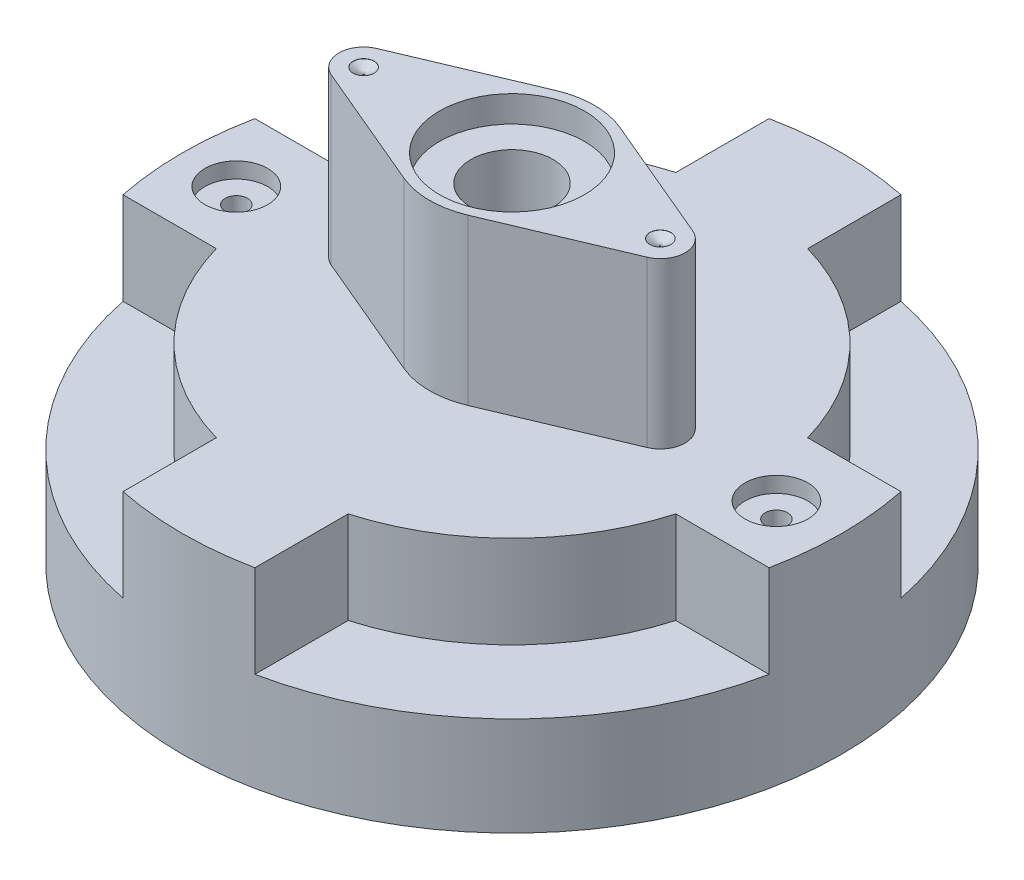
SolidWorks part; units mm, degrees
ref_plane "Front Plane" through (0, 0, 0) normal (0, 0, 1) x (1, 0, 0)
ref_plane "Top Plane" through (0, 0, 0) normal (0, 1, 0) x (1, 0, 0)
ref_plane "Right Plane" through (0, 0, 0) normal (1, 0, 0) x (0, 0, -1)
sketch "Sketch2" plane through (0, 0, 0) normal (0, 1, 0) x (1, 0, 0)
  circle A0 centre (0, 0) radius 100
  dimension "D1" = 200
extrude "Boss-Extrude1" add sketch "Sketch2" along normal blind 30
sketch "Sketch3" plane through (0, 30, 0) normal (0, 1, 0) x (1, 0, 0)
  line L0 (-20, 97.9796) -> (-20, 69.6868)
  line L2 (20, 69.6868) -> (20, 97.9796)
  line L3 (97.9796, 20) -> (69.6868, 20)
  line L4 (69.6868, -20) -> (97.9796, -20)
  line L5 (20, -97.9796) -> (20, -69.6868)
  line L6 (-20, -69.6868) -> (-20, -97.9796)
  line L7 (-97.9796, -20) -> (-69.6868, -20)
  line L8 (-69.6868, 20) -> (-97.9796, 20)
  arc A0 (-20, 69.6868) -> (-69.6868, 20) centre (0, 0) ccw
  circle A1 centre (0, 0) radius 100 construction
  arc A2 (20, 97.9796) -> (-20, 97.9796) centre (0, 0) ccw
  arc A3 (-20, 97.9796) -> (20, 97.9796) centre (0, 0) cw
  arc A4 (97.9796, -20) -> (97.9796, 20) centre (0, 0) ccw
  arc A5 (-20, -97.9796) -> (20, -97.9796) centre (0, 0) ccw
  arc A6 (-97.9796, 20) -> (-97.9796, -20) centre (0, 0) ccw
  arc A7 (-69.6868, -20) -> (-20, -69.6868) centre (0, 0) ccw
  arc A8 (69.6868, 20) -> (20, 69.6868) centre (0, 0) ccw
  arc A9 (20, -69.6868) -> (69.6868, -20) centre (0, 0) ccw
  point P23 (0, 0)
  circle M3 centre (0, 0) radius 100
  dimension "D1" = 145
  dimension "D2" = 20
  dimension "D3" = 4
extrude "Boss-Extrude2" add sketch "Sketch3" along normal blind 28 contours L5 A9 L4 L3 A8 L2 L0 A0 L8 L7 A7 L6 M3
sketch "Sketch4" plane through (0, 58, 0) normal (0, 1, 0) x (1, 0, 0)
  line L0 (0, 25) -> (0, 0) construction
  line L1 (0, 0) -> (-45, 0) construction
  line L2 (-9.7222, 23.0321) -> (-47.9167, 6.9096)
  line L4 (-9.7222, -23.0321) -> (-47.9167, -6.9096)
  line L5 (9.7222, -23.0321) -> (47.9167, -6.9096)
  line L6 (9.7222, 23.0321) -> (47.9167, 6.9096)
  arc A0 (-9.7222, -23.0321) -> (9.7222, -23.0321) centre (0, 0) ccw
  arc A1 (47.9167, -6.9096) -> (47.9167, 6.9096) centre (45, 0) ccw
  arc A2 (-47.9167, 6.9096) -> (-47.9167, -6.9096) centre (-45, 0) ccw
  arc A3 (9.7222, 23.0321) -> (-9.7222, 23.0321) centre (0, 0) ccw
  point P1 (-159.8405, 52.7409)
  point P4 (0, 0)
  point P6 (0, 0)
  dimension "D1" = 50
  dimension "D2" = 15
  dimension "D3" = 45
extrude "Boss-Extrude3" add sketch "Sketch4" along normal blind 50
hole_wizard "CBORE for 1/4 Hex Head Bolt1" positions "3DSketch2" profile "Sketch6" counterbore size "1/4" standard "ANSI Inch" end condition up to next
sketch3d "3DSketch2"
  point P0 (-82.9555, 58, 0.659)
  point P2 (81.5405, 58, 1.3294)
sketch "Sketch6" plane through (-82.9555, 58, 0.659) normal (1, 0, 0) x (0, 0, 1)
  line L0 (0, 0) -> (0, 58)
  line L1 (0, 58) -> (3.3782, 58)
  line L3 (3.3782, 58) -> (3.3782, 4.7752)
  line L4 (3.3782, 4.7752) -> (9.525, 4.7752)
  line L5 (9.525, 4.7752) -> (9.525, 0)
  line L7 (9.525, 0) -> (0, 0)
  line L11 (0, -6.35) -> (0, 107.95) construction
  dimension "Thru Hole Dia." = 6.7564
  dimension "Thru Hole Depth" = 58
  dimension "C'Bore Dia." = 19.05
  dimension "C'Bore Depth" = 4.7752
hole_wizard "1/4 (0.25) Diameter Hole1" positions "3DSketch3" profile "Sketch8" hole size "1/4" standard "ANSI Inch"
sketch3d "3DSketch3"
  line L0 (-45, 108, 0) -> (-45, 58, 0) construction
  point P0 (-45, 108, 0)
sketch "Sketch8" plane through (-45, 108, 0) normal (1, 0, 0) x (0, 0, 1)
  line L0 (0, 0) -> (0, 1.9577)
  line L1 (0, 1.9577) -> (3.175, 0.05)
  line L2 (3.175, 0.05) -> (3.175, 0)
  line L5 (3.175, 0) -> (0, 0)
  line L10 (0, 1.9577) -> (-3.175, 0.05) construction
  line L11 (0, -6.35) -> (0, 107.95) construction
  dimension "Hole Dia." = 6.35
  dimension "Hole Depth" = 0.05
  dimension "Drill Angle" = 118
mirror "Mirror1" about plane through (0, 0, 0) normal (1, 0, 0) of "1/4 (0.25) Diameter Hole1"
sketch "Sketch9" plane through (0, 0, 0) normal (0, 0, 1) x (1, 0, 0)
  line L0 (0, 0) -> (0, 108) construction
  line L1 (-100, 0) -> (100, 0) construction
  line L2 (9.7222, 108) -> (-9.7222, 108) construction
  line L3 (0, 108) -> (-22, 108)
  line L4 (-9.7222, 108) -> (-47.9167, 108) construction
  line L5 (-22, 108) -> (-22, 100)
  line L6 (-22, 100) -> (-12.5, 100)
  line L7 (-12.5, 100) -> (-12.5, 62)
  line L8 (-12.5, 62) -> (-5, 62)
  line L9 (-5, 62) -> (-5, 49)
  line L10 (-5, 49) -> (-15.7899, 49)
  line L11 (-28, 36.7899) -> (-28, 25)
  line L12 (-28, 25) -> (-40, 25)
  line L13 (-40, 25) -> (-40, 0)
  line L15 (-40, 0) -> (0, 0)
  line L16 (0, 0) -> (0, 108)
  arc A0 (-15.7899, 49) -> (-28, 36.7899) centre (-15.7899, 36.7899) ccw
  dimension "D9" = 10
  dimension "D10" = 12.2101
  dimension "D2" = 8
  dimension "D3" = 38
  dimension "D4" = 24
  dimension "D5" = 56
  dimension "D6" = 80
  dimension "D7" = 25
  dimension "D8" = 25
  dimension "D11" = 44
revolve "Cut-Revolve1" cut sketch "Sketch9" angle 360 about L0
